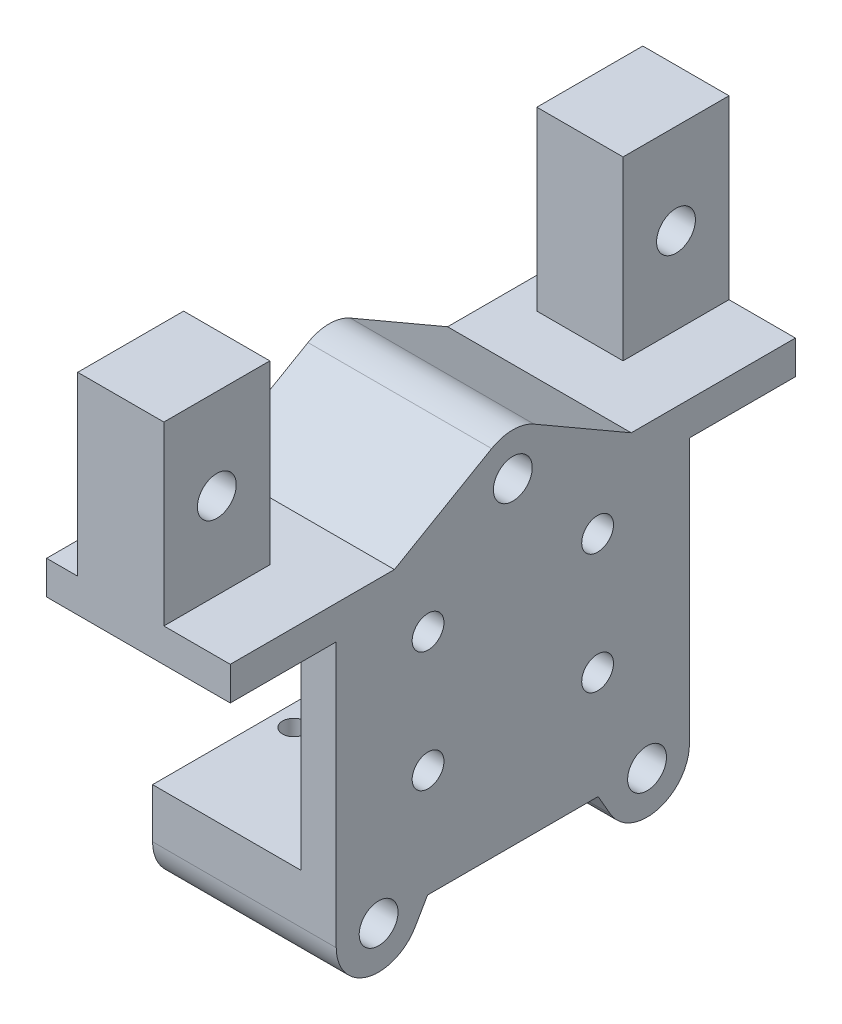
SolidWorks part; units mm, degrees
material "PET"
ref_plane "Front Plane" through (0, 0, 0) normal (0, 0, 1) x (1, 0, 0)
ref_plane "Top Plane" through (0, 0, 0) normal (0, 1, 0) x (1, 0, 0)
ref_plane "Right Plane" through (0, 0, 0) normal (1, 0, 0) x (0, 0, -1)
sketch "Sketch1" plane through (0, 0, 0) normal (0, 0, 1) x (1, 0, 0)
  line L0 (-10.5, 0) -> (15.5, 0)
  line L1 (15.5, 0) -> (15.5, 42.25)
  line L2 (15.5, 42.25) -> (-10.5, 42.25)
  line L3 (10.5, 37.5) -> (10.5, 7)
  line L4 (10.5, 7) -> (-10.5, 7)
  line L8 (-10.5, 7) -> (-10.5, 0)
  line L9 (10.5, 37.5) -> (-10.5, 37.5)
  line L10 (-10.5, 37.5) -> (-10.5, 42.25)
  line L11 (0, 0) -> (0, 42.7189) construction
  point P11 (0, 7)
  dimension "D2" = 21
  dimension "D3" = 5
  dimension "D4" = 7
  dimension "D5" = 30.5
  dimension "D6" = 35.25
extrude "Boss-Extrude1" add sketch "Sketch1" along normal blind 50
sketch "Sketch2" plane through (0, 0, 0) normal (0, -1, 0) x (1, 0, 0)
  line L0 (-10.5, 50) -> (-10.5, 0) construction
  line L3 (-7.5, 17) -> (7.5, 17) construction
  line L4 (-7.5, 17) -> (-7.5, 33) construction
  line L5 (-7.5, 33) -> (7.5, 33) construction
  line L6 (7.5, 17) -> (7.5, 33) construction
  line L7 (-7.5, 17) -> (7.5, 33) construction
  line L8 (-7.5, 33) -> (7.5, 17) construction
  point P5 (0, 25)
  dimension "D1" = 15
  dimension "D2" = 16
  dimension "D3" = 10.5
  dimension "D4" = 25
hole_wizard "Ø3.2 (3.2) Diameter Hole1" positions "Sketch3" profile "Sketch4" hole size "Ø3.2" standard "ANSI Metric"
sketch "Sketch3" plane through (0, 0, 0) normal (0, -1, 0) x (-1, 0, 0)
  point P0 (-7.5, -17)
  point P3 (7.5, -17)
  point P6 (7.5, -33)
  point P9 (-7.5, -33)
sketch "Sketch4" plane through (7.5, 0, 17) normal (1, 0, 0) x (0, 0, -1)
  line L0 (0, 0) -> (0, 7)
  line L1 (0, 7) -> (1.6, 7)
  line L2 (1.6, 7) -> (1.6, 0)
  line L5 (1.6, 0) -> (0, 0)
  line L11 (0, -6.35) -> (0, 107.95) construction
  dimension "Thru Hole Dia." = 3.2
  dimension "Thru Hole Depth" = 7
sketch "Sketch5" plane through (15.5, 0, 0) normal (1, 0, 0) x (0, 0, -1)
  line L0 (-50, 32.25) -> (0, 32.25) construction
  line L1 (-50, 0) -> (-50, 42.25) construction
  line L2 (0, 0) -> (0, 42.25) construction
  line L3 (-50, 42.25) -> (0, 42.25) construction
  line L4 (-50, 15.25) -> (0, 15.25) construction
  line L5 (-13, 32.25) -> (-13, 15.25) construction
  line L6 (-37, 32.25) -> (-37, 15.25) construction
  circle A0 centre (-37, 32.25) radius 2.25
  circle A1 centre (-13, 32.25) radius 2.25
  circle A2 centre (-37, 15.25) radius 2.25
  circle A3 centre (-13, 15.25) radius 2.25
  point P12 (-25, 32.25)
  dimension "D2" = 12
  dimension "D3" = 12
  dimension "D4" = 4.5
  dimension "D5" = 4.5
  dimension "D7" = 4.5
  dimension "D8" = 4.5
  dimension "D1" = 10
  dimension "D6" = 17
extrude "Cut-Extrude1" cut sketch "Sketch5" against normal through all
sketch "Sketch6" plane through (15.5, 0, 0) normal (1, 0, 0) x (0, 0, -1)
  line L1 (-50, 42.25) -> (-65, 42.25)
  line L2 (-50, 42.25) -> (-50, 37.5)
  line L3 (-50, 37.5) -> (-65, 37.5)
  line L4 (-65, 42.25) -> (-65, 37.5)
  line L5 (0, 42.25) -> (15, 42.25)
  line L6 (0, 42.25) -> (0, 37.5)
  line L7 (0, 37.5) -> (15, 37.5)
  line L8 (15, 42.25) -> (15, 37.5)
  dimension "D1" = 4.75
  dimension "D2" = 15
  dimension "D3" = 15
extrude "Boss-Extrude2" add sketch "Sketch6" against normal up to surface (26 mm away) up to face at (-10.5, 39.875, 25)
ref_plane "Plane1" through (0, 0, 25) normal (0, 0, -1) x (-1, 0, 0)
sketch "Sketch8" plane through (0, 42.25, 0) normal (0, 1, 0) x (1, 0, 0)
  line L0 (-10.5, 15) -> (15.5, 15) construction
  line L1 (-6.1, 15) -> (6.1, 15)
  line L2 (-6.1, 15) -> (-6.1, 0)
  line L3 (-6.1, 0) -> (6.1, 0)
  line L4 (6.1, 15) -> (6.1, 0)
  line L5 (-10.5, -65) -> (15.5, -65) construction
  line L6 (-6.1, -65) -> (6.1, -65)
  line L7 (-6.1, -65) -> (-6.1, -50)
  line L8 (-6.1, -50) -> (6.1, -50)
  line L9 (6.1, -65) -> (6.1, -50)
  line L10 (-10.5, -65) -> (-10.5, 15) construction
  dimension "D1" = 15
  dimension "D2" = 15
  dimension "D3" = 4.4
  dimension "D4" = 12.2
extrude "Boss-Extrude3" add sketch "Sketch8" along normal blind 25
sketch "Sketch9" plane through (-6.1, 0, 0) normal (-1, 0, 0) x (0, 0, 1)
  line L0 (-7.5, 67.25) -> (-7.5, 42.25) construction
  line L1 (-15, 67.25) -> (0, 67.25) construction
  line L2 (-15, 42.25) -> (0, 42.25) construction
  line L3 (57.5, 67.25) -> (57.5, 42.25) construction
  line L4 (50, 67.25) -> (65, 67.25) construction
  line L5 (50, 42.25) -> (65, 42.25) construction
  line L6 (-7.5, 54.45) -> (57.5, 54.45) construction
  circle A0 centre (-7.5, 54.45) radius 2.75
  circle A1 centre (57.5, 54.45) radius 2.75
  dimension "D2" = 5.5
  dimension "D3" = 5.5
  dimension "D1" = 12.2
extrude "Cut-Extrude2" cut sketch "Sketch9" against normal through all
sketch "Sketch10" plane through (-10.5, 0, 0) normal (-1, 0, 0) x (0, 0, 1)
  line L0 (50, 0) -> (0, 0) construction
  line L1 (0, 7) -> (0, 0) construction
  line L2 (11.1962, -3) -> (12.9282, 0)
  line L3 (25, 0) -> (25, 45) construction
  line L4 (22, 50.1962) -> (8.2369, 42.25)
  line L5 (65, 42.25) -> (-15, 42.25) construction
  line L6 (28, 50.1962) -> (41.7631, 42.25)
  line L7 (38.8038, -3) -> (37.0718, 0)
  line L8 (0, 0) -> (12.9282, 0)
  line L9 (37.0718, 0) -> (50, 0)
  line L10 (8.2369, 42.25) -> (41.7631, 42.25)
  arc A0 (0, 0) -> (11.1962, -3) centre (6, 0) ccw
  arc A1 (38.8038, -3) -> (50, 0) centre (44, 0) ccw
  arc A2 (28, 50.1962) -> (22, 50.1962) centre (25, 45) ccw
  dimension "D1" = 12
  dimension "D2" = 12
  dimension "D3" = 12
  dimension "D4" = 45
  dimension "D5" = 30
  dimension "D6" = 30
  dimension "D7" = 60
  dimension "D8" = 60
extrude "Boss-Extrude4" add sketch "Sketch10" against normal up to surface (26 mm away) up to face at (15.5, 34.5, 13)
sketch "Sketch11" plane through (-10.5, 0, 0) normal (-1, 0, 0) x (0, 0, 1)
  circle A0 centre (25, 45) radius 2.75
  circle A1 centre (44, 0) radius 2.75
  circle A2 centre (6, 0) radius 2.75
  dimension "D1" = 5.5
  dimension "D2" = 5.5
  dimension "D3" = 5.5
extrude "Cut-Extrude3" cut sketch "Sketch11" against normal up to next
